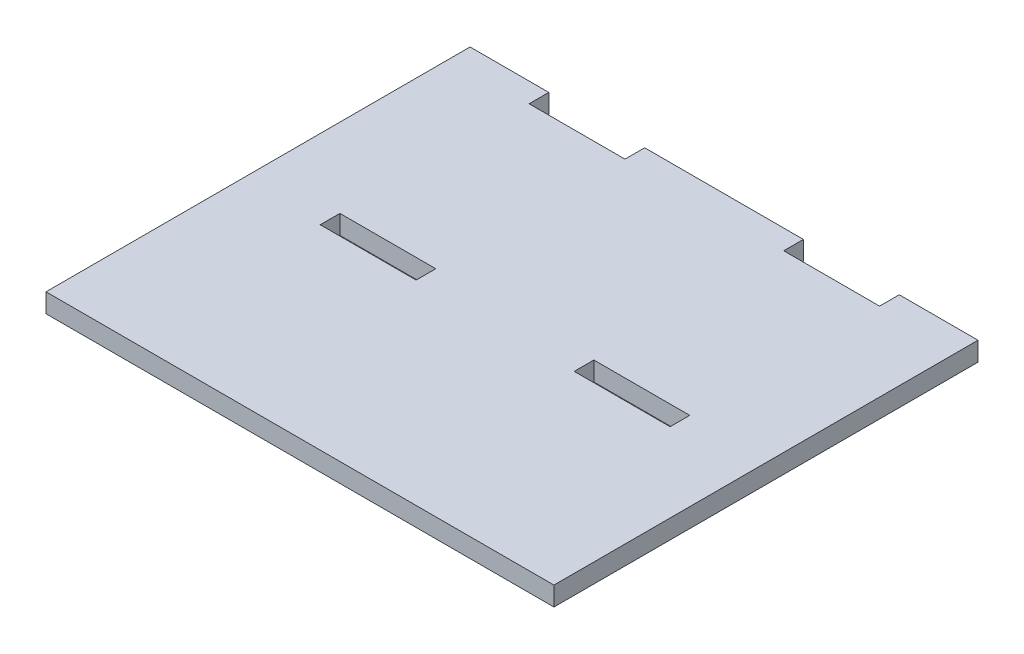
SolidWorks part; units mm, degrees
ref_plane "Front Plane" through (0, 0, 0) normal (0, 0, 1) x (1, 0, 0)
ref_plane "Top Plane" through (0, 0, 0) normal (0, 1, 0) x (1, 0, 0)
ref_plane "Right Plane" through (0, 0, 0) normal (1, 0, 0) x (0, 0, -1)
sketch "Sketch2" plane through (0, 0, 0) normal (0, 1, 0) x (1, 0, 0)
  line L0 (0, 33.395) -> (80, 33.395) construction
  line L29 (0, 0) -> (80, 0)
  line L30 (0, 0) -> (0, 66.79)
  line L47 (0, 66.79) -> (12.4, 66.79)
  line L65 (80, 0) -> (80, 66.79)
  line L66 (12.45, 33.84) -> (27.55, 33.84)
  line L67 (12.45, 33.84) -> (12.45, 30.74)
  line L68 (12.45, 30.74) -> (27.55, 30.74)
  line L69 (27.55, 33.84) -> (27.55, 30.74)
  line L74 (40, 66.79) -> (40, 0) construction
  line L76 (12.4, 66.79) -> (12.4, 63.69)
  line L77 (12.4, 63.69) -> (27.5, 63.69)
  line L78 (27.5, 66.79) -> (27.5, 63.69)
  line L79 (67.55, 30.74) -> (52.45, 30.74)
  line L80 (52.45, 33.84) -> (52.45, 30.74)
  line L81 (67.55, 33.84) -> (52.45, 33.84)
  line L82 (67.55, 33.84) -> (67.55, 30.74)
  line L83 (67.6, 63.69) -> (52.5, 63.69)
  line L84 (52.5, 66.79) -> (52.5, 63.69)
  line L86 (67.6, 66.79) -> (67.6, 63.69)
  line L87 (67.6, 66.79) -> (80, 66.79)
  line L88 (27.5, 66.79) -> (52.5, 66.79)
  dimension "D1" = 80
  dimension "D2" = 66.79
  dimension "D3" = 15.1
  dimension "D4" = 3.1
  dimension "D5" = 12.45
  dimension "D6" = 30.74
  dimension "D7" = 15.1
  dimension "D8" = 3.1
extrude "Boss-Extrude5" add sketch "Sketch2" along normal blind 3
